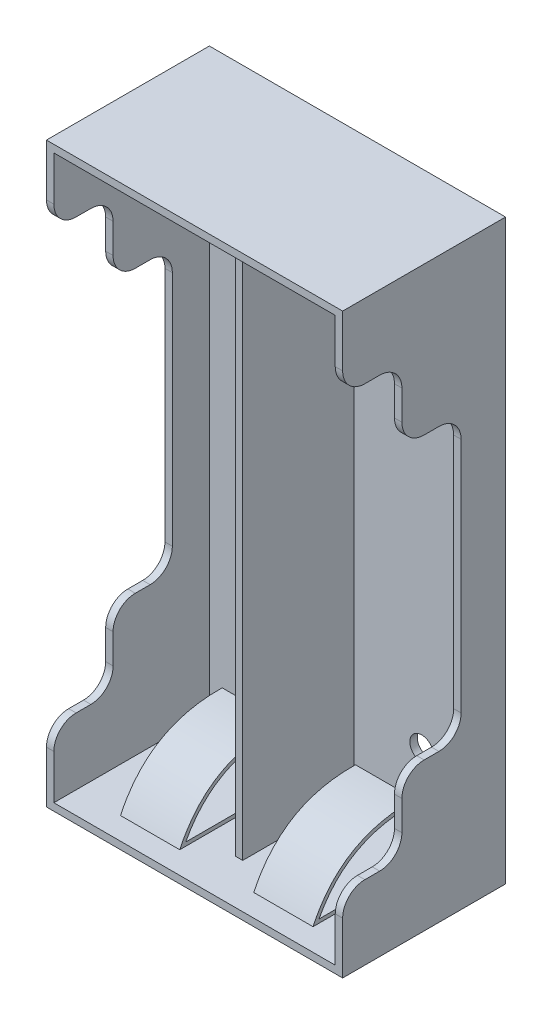
SolidWorks part; units mm, degrees
ref_plane "Front Plane" through (0, 0, 0) normal (0, 0, 1) x (1, 0, 0)
ref_plane "Top Plane" through (0, 0, 0) normal (0, 1, 0) x (1, 0, 0)
ref_plane "Right Plane" through (0, 0, 0) normal (1, 0, 0) x (0, 0, -1)
sketch "Sketch1" plane through (0, 0, 0) normal (0, 0, 1) x (1, 0, 0)
  line L1 (0, 0) -> (40, 0)
  line L2 (0, 0) -> (0, 78)
  line L3 (0, 78) -> (40, 78)
  line L4 (40, 0) -> (40, 78)
  dimension "D1" = 40
  dimension "78" = 78
extrude "Boss-Extrude1" add sketch "Sketch1" along normal blind 22
shell "Shell1" thickness 1
sketch "Sketch2" plane through (40, 0, 0) normal (1, 0, 0) x (0, 0, -1)
  line L0 (-35.763, 39) -> (0, 39) construction
  line L1 (0, 0) -> (0, 78) construction
  line L2 (-22, 10) -> (-14, 10)
  line L3 (-22, 0) -> (-22, 78) construction
  line L4 (-14, 10) -> (-14, 20)
  line L5 (-14, 20) -> (-6, 20)
  line L6 (-6, 20) -> (-6, 58)
  line L7 (-22, 10) -> (-22, 68)
  line L8 (-14, 58) -> (-6, 58)
  line L9 (-14, 68) -> (-14, 58)
  line L10 (-22, 68) -> (-14, 68)
  point P14 (-22, 39)
  point P15 (-6, 39)
  dimension "D1" = 10
  dimension "D2" = 8
  dimension "D3" = 10
  dimension "D4" = 8
extrude "Cut-Extrude1" cut sketch "Sketch2" against normal up to surface (40 mm away) up to face at (0, 39, 11)
fillet "Fillet1" radius 3 16 edges at (0.5, 10, 22) (0.5, 10, 14) (0.5, 20, 14) (0.5, 20, 6) (0.5, 68, 22) (0.5, 68, 14) (0.5, 58, 14) (0.5, 58, 6) (39.5, 68, 22) (39.5, 68, 14) (39.5, 58, 14) (39.5, 58, 6) (39.5, 20, 6) (39.5, 20, 14) (39.5, 10, 14) (39.5, 10, 22)
ref_plane "Plane1" through (20, 0, 0) normal (1, 0, 0) x (0, 0, -1)
sketch "Sketch3" plane through (20, 0, 0) normal (1, 0, 0) x (0, 0, -1)
  line L0 (-1, 1) -> (-19, 1)
  line L1 (-1, 77) -> (-1, 1) construction
  line L2 (-22, 1) -> (-1, 1) construction
  line L3 (-1, 1) -> (-1, 1.5)
  line L4 (-1, 1.5) -> (-18.1932, 1.5)
  line L5 (-5.2747, 8.5671) -> (-5.2655, 9.067)
  line L6 (-29.8276, 39) -> (0, 39) construction
  line L7 (0, 78) -> (0, 0) construction
  line L8 (-1, 1.5) -> (-15.0102, 2) construction
  line L9 (-15.0191, 1.5) -> (-18.1932, 1.5) construction
  line L10 (-15.0191, 1.5) -> (-15.028, 1.5003) construction
  line L11 (-15.0191, 1.5) -> (-15.0191, 1.5) construction
  line L12 (-5.2747, 69.4329) -> (-5.2655, 68.933)
  line L13 (-1, 76.5) -> (-18.1932, 76.5)
  line L14 (-1, 77) -> (-1, 76.5)
  line L15 (-1, 77) -> (-19, 77)
  spline S0 degree 2 poles (-19, 1) (-15.1298, 9.2497) (-5.2655, 9.067) knots 0 0 0 1 1 1
  spline S1 degree 1 poles (-18.1932, 1.5) (-5.2747, 8.5671) knots 0 0 1 1 construction
  spline S2 degree 2 poles (-18.1932, 1.5) (-16.7534, 4.2267) (-13.159, 6.9962) (-8.7281, 8.6269) (-5.2747, 8.5671) knots 0.045483 0.045483 0.045483 0.403427 0.642056 1 1 1
  spline S3 degree 2 poles (-18.1932, 76.5) (-13.6926, 70.1244) (-5.2747, 69.4329) knots 0.057815 0.057815 0.057815 1 1 1
  spline S4 degree 2 poles (-19, 77) (-15.1298, 68.7503) (-5.2655, 68.933) knots 0 0 0 1 1 1
  dimension "D1" = 0.5
  dimension "D3" = 18
  dimension "D2" = 0.5
extrude "Boss-Extrude2" add sketch "Sketch3" along normal mid plane 26
sketch "Sketch4" plane through (0, 0, 22) normal (0, 0, 1) x (1, 0, 0)
  line L0 (33, 1) -> (7, 1) construction
  line L1 (25, 1) -> (15, 1)
  line L2 (25, 1) -> (25, 11)
  line L3 (25, 11) -> (15, 11)
  line L4 (15, 1) -> (15, 11)
  line L5 (33, 1) -> (33, 9.071) construction
  line L6 (7, 9.071) -> (7, 1) construction
  line L7 (40, 39) -> (0, 39) construction
  line L8 (40, 23) -> (40, 55) construction
  line L9 (0, 55) -> (0, 23) construction
  line L10 (15, 77) -> (15, 67)
  line L11 (25, 67) -> (15, 67)
  line L12 (25, 77) -> (25, 67)
  line L13 (25, 77) -> (15, 77)
  dimension "D1" = 8
  dimension "8" = 8
  dimension "D2" = 10
extrude "Cut-Extrude2" cut sketch "Sketch4" against normal up to surface (21 mm away) up to face at (20, 39, 1)
sketch "Sketch6" plane through (0, 0, 1) normal (0, 0, 1) x (1, 0, 0)
  line L0 (25, 77) -> (15, 77) construction
  line L1 (20.5, 77) -> (19.5, 77)
  line L2 (20.5, 77) -> (20.5, 1)
  line L3 (20.5, 1) -> (19.5, 1)
  line L4 (19.5, 77) -> (19.5, 1)
  line L5 (1, 1) -> (39, 1) construction
  line L6 (40, 71) -> (40, 78) construction
  dimension "D1" = 1
  dimension "D2" = 19.5
extrude "Boss-Extrude3" add sketch "Sketch6" along normal blind 15
sketch "Sketch7" plane through (0, 0, 1) normal (0, 0, 1) x (1, 0, 0)
  line L0 (0, 0) -> (40, 0) construction
  line L4 (40, 13) -> (40, 17) construction
  circle A0 centre (10.325, 11.175) radius 1.6
  circle A2 centre (10.325, 66.825) radius 1.6
  circle A3 centre (29.675, 11.175) radius 1.6
  circle A4 centre (29.675, 66.825) radius 1.6
  dimension "D1" = 3.2
  dimension "D4" = 2
  dimension "D6" = 19.35
  dimension "D3" = 11.175
  dimension "D5" = 55.65
  dimension "D7" = 10.325
  dimension "D2" = 2
extrude "Cut-Extrude3" cut sketch "Sketch7" against normal blind 15
